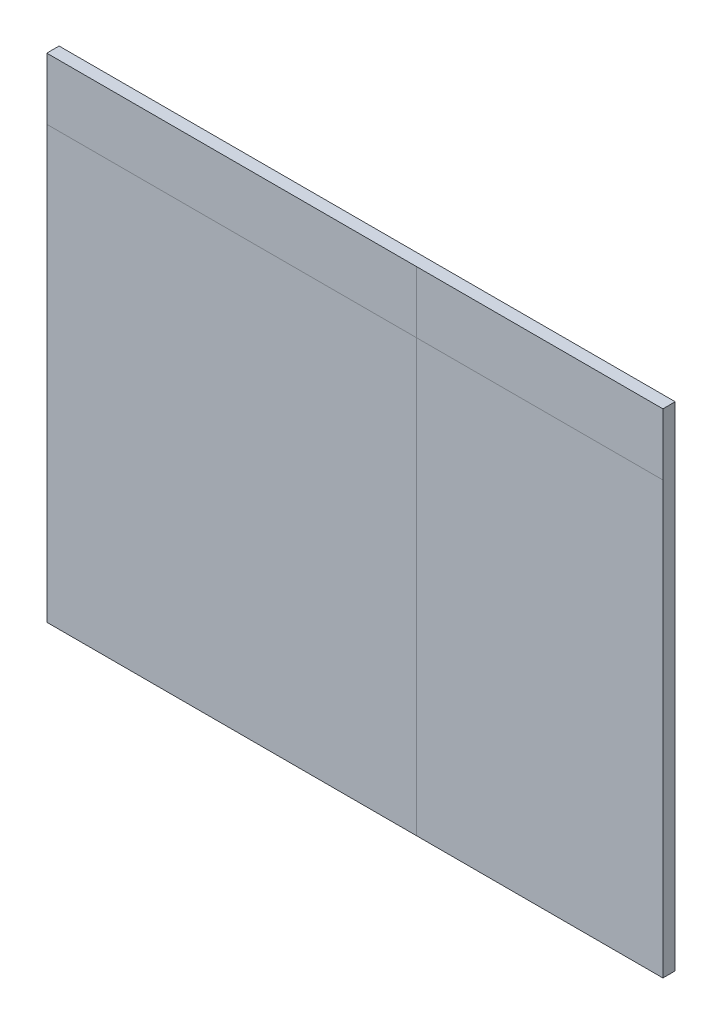
SolidWorks part; units mm, degrees
ref_plane "Front Plane" through (0, 0, 0) normal (0, 0, 1) x (1, 0, 0)
ref_plane "Top Plane" through (0, 0, 0) normal (0, 1, 0) x (1, 0, 0)
ref_plane "Right Plane" through (0, 0, 0) normal (1, 0, 0) x (0, 0, -1)
other "Configuration Table"
sketch "Sketch1" plane through (0, 0, 0) normal (0, 0, 1) x (1, 0, 0)
  line L1 (0, -75446.5262) -> (-200000, -75446.5262)
  line L2 (0, -75446.5262) -> (0, 84553.4738)
  line L3 (0, 84553.4738) -> (-200000, 84553.4738)
  line L4 (-200000, -75446.5262) -> (-200000, 84553.4738)
  point P0 (0, 0)
  dimension "D1" = 160000
  dimension "D2" = 200000
extrude "Extrude1" add sketch "Sketch1" along normal blind 4000
ref_plane "Plane1" through (0, 0, 10000) normal (0, 0, 1) x (1, 0, 0)
sketch "Sketch2" plane through (0, 0, 10000) normal (0, 0, 1) x (1, 0, 0)
  line L0 (-80000, 84553.4738) -> (-80000, -75446.5262)
split line "Split Line1"
sketch "Sketch4" plane through (0, 0, 10000) normal (0, 0, 1) x (1, 0, 0)
  line L0 (-200000, 64553.4738) -> (0, 64553.4738)
split line "Split Line2"
